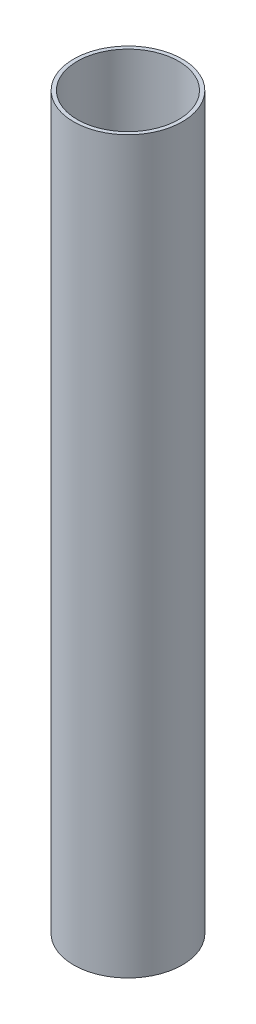
SolidWorks part; units mm, degrees
material "S-Glass Fiber"
ref_plane "Front Plane" through (0, 0, 0) normal (0, 0, 1) x (1, 0, 0)
ref_plane "Top Plane" through (0, 0, 0) normal (0, 1, 0) x (1, 0, 0)
ref_plane "Right Plane" through (0, 0, 0) normal (1, 0, 0) x (0, 0, -1)
sketch "Sketch1" plane through (0, 0, 0) normal (0, 1, 0) x (1, 0, 0)
  circle A0 centre (0, 0) radius 19.3675
  circle A1 centre (0, 0) radius 20.8
  dimension "D1" = 38.735
  dimension "D2" = 41.6
extrude "Boss-Extrude1" add sketch "Sketch1" along normal blind 279.4
